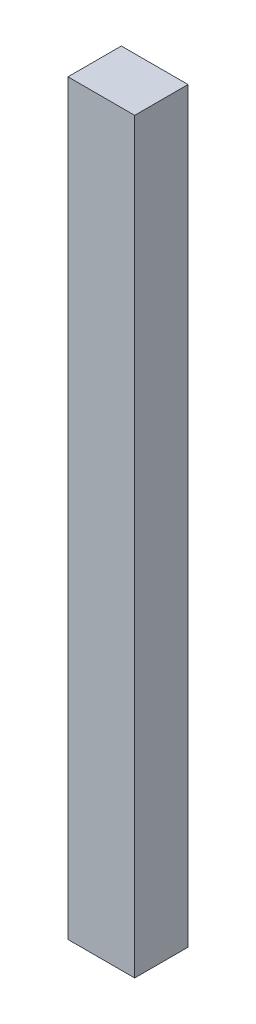
SolidWorks part; units mm, degrees
ref_plane "Front Plane" through (0, 0, 0) normal (0, 0, 1) x (1, 0, 0)
ref_plane "Top Plane" through (0, 0, 0) normal (0, 1, 0) x (1, 0, 0)
ref_plane "Right Plane" through (0, 0, 0) normal (1, 0, 0) x (0, 0, -1)
other "Configuration Table"
sketch "Sketch1" plane through (0, 0, 0) normal (0, 1, 0) x (1, 0, 0)
  line L0 (615, -40) -> (615, -20)
  line L1 (615, -20) -> (640, -20)
  line L2 (640, -20) -> (640, -40)
  line L3 (640, -40) -> (615, -40)
extrude "FKAP_cerceve_sag_1" add sketch "Sketch1" along normal blind 280 separate body
